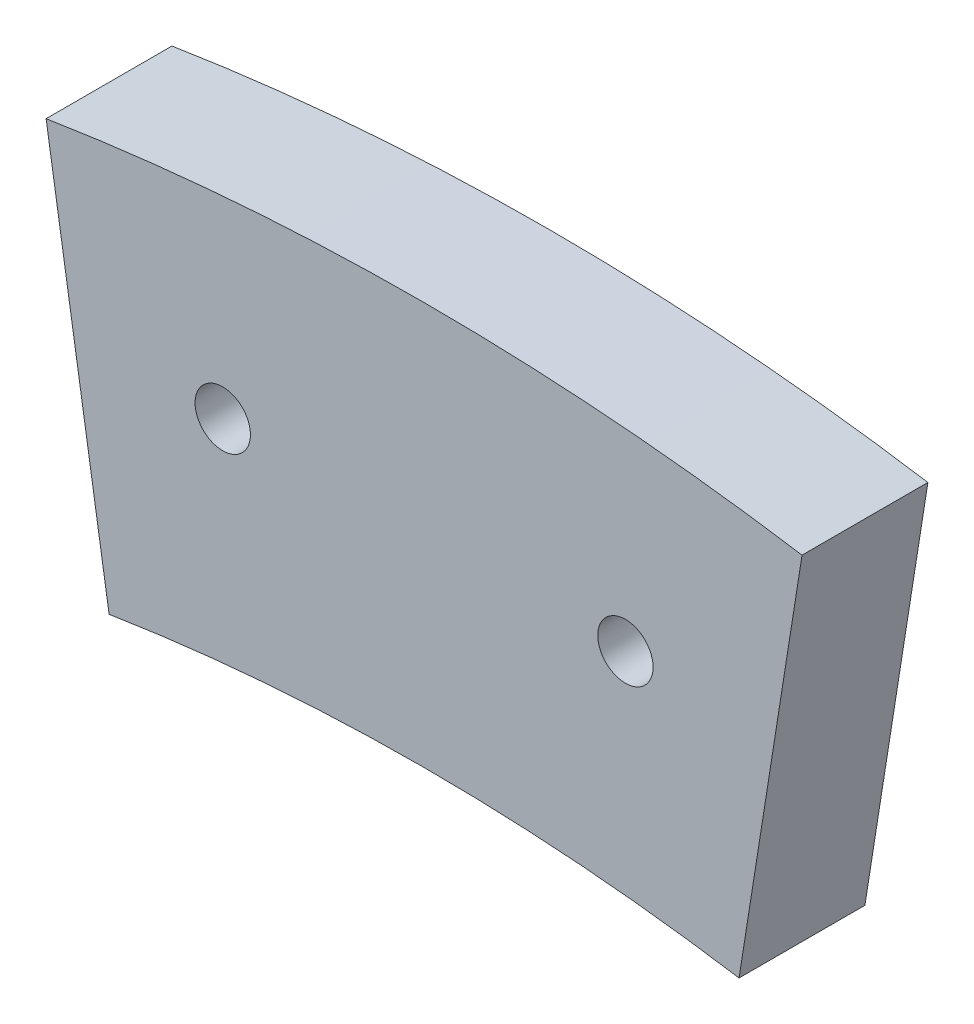
SolidWorks part; units mm, degrees
ref_plane "Front Plane" through (0, 0, 0) normal (0, 0, 1) x (1, 0, 0)
ref_plane "Top Plane" through (0, 0, 0) normal (0, 1, 0) x (1, 0, 0)
ref_plane "Right Plane" through (0, 0, 0) normal (1, 0, 0) x (0, 0, -1)
sketch "Sketch1" plane through (0, 0, 0) normal (0, 0, 1) x (1, 0, 0)
  line L0 (0, 0) -> (0, 96) construction
  line L1 (0, 0) -> (32.8339, 90.2105) construction
  line L2 (0, 0) -> (-6.116, 6.116) construction
  line L3 (0, 0) -> (-83.1384, 48) construction
  line L4 (-83.1384, 48) -> (-69.282, 40)
  line L5 (27.3616, 75.1754) -> (32.8339, 90.2105)
  line L6 (0, 0) -> (-15.0177, 94.8181) construction
  line L7 (0, 0) -> (15.0177, 94.8181) construction
  line L8 (0, 0) -> (-75.4804, 49.0175) construction
  line L9 (0, 0) -> (26.3135, 86.0674) construction
  line L10 (-15.0177, 94.8181) -> (-12.5148, 79.0151)
  line L11 (15.0177, 94.8181) -> (12.5148, 79.0151)
  line L12 (-27.3616, 75.1754) -> (0, 96) construction
  line L13 (-27.3616, 75.1754) -> (0, 96) construction
  line L14 (-21.1802, 88) -> (8, 88) construction
  line L15 (-75.4804, 49.0175) -> (-72.1257, 46.839)
  line L16 (-50.4006, 88.6785) -> (-43.5134, 76.5054)
  line L17 (0, 0) -> (-28.7074, 81.0672) construction
  line L18 (-30.0426, 84.8377) -> (-32.0455, 90.4936) construction
  line L19 (-34.2514, 96.1237) -> (-29.5682, 82.8988)
  line L20 (-34.2514, 96.1237) -> (-33.8743, 96.2573)
  line L22 (-33.8743, 96.2573) -> (-29.1911, 83.0323)
  line L23 (-34.2514, 96.1237) -> (-29.8395, 84.8634) construction
  line L24 (-30.2166, 84.7299) -> (-33.8743, 96.2573) construction
  line L25 (-25.3461, 98.8012) -> (-21.8442, 85.2603)
  line L26 (-25.7334, 98.7011) -> (-22.2314, 85.1601)
  line L27 (-22.7288, 87.0833) -> (-22.3416, 87.1834)
  line L28 (-16.6396, 100.6344) -> (-14.3311, 86.8395)
  line L29 (-17.0663, 100.563) -> (-14.7579, 86.768)
  line L30 (-14.6614, 88.7978) -> (-14.659, 88.799)
  line L31 (-25.7334, 98.7011) -> (-25.3461, 98.8012)
  line L32 (-17.0663, 100.563) -> (-16.6396, 100.6344)
  line L33 (-37.1397, 81.9801) -> (-37.5037, 81.8143)
  line L38 (-42.48, 92.7338) -> (-36.6799, 80.0067)
  line L39 (-42.116, 92.8997) -> (-36.3159, 80.1726)
  line L40 (-42.116, 92.8997) -> (-42.48, 92.7338)
  line L41 (42.116, 92.8997) -> (36.3159, 80.1726)
  line L42 (42.48, 92.7338) -> (36.6799, 80.0067)
  line L44 (44.4908, 78.2349) -> (44.4904, 78.2343)
  line L45 (44.4882, 78.2355) -> (44.4908, 78.2349)
  line L46 (37.1397, 81.9801) -> (37.5037, 81.8143)
  line L47 (17.0663, 100.563) -> (16.6396, 100.6344)
  line L48 (17.0663, 100.563) -> (14.7579, 86.768)
  line L49 (16.6396, 100.6344) -> (14.3311, 86.8395)
  line L50 (30.2166, 84.7299) -> (33.8743, 96.2573) construction
  line L51 (34.2514, 96.1237) -> (29.8395, 84.8634) construction
  line L52 (30.0426, 84.8377) -> (32.0455, 90.4936) construction
  line L53 (42.116, 92.8997) -> (42.48, 92.7338)
  line L55 (25.7334, 98.7011) -> (25.3461, 98.8012)
  line L56 (14.6614, 88.7978) -> (14.659, 88.799)
  line L57 (22.7288, 87.0833) -> (22.3416, 87.1834)
  line L58 (25.7334, 98.7011) -> (22.2314, 85.1601)
  line L59 (25.3461, 98.8012) -> (21.8442, 85.2603)
  line L60 (33.8743, 96.2573) -> (29.1911, 83.0323)
  line L62 (34.2514, 96.1237) -> (33.8743, 96.2573)
  line L63 (34.2514, 96.1237) -> (29.5682, 82.8988)
  line L64 (-29.3797, 82.9658) -> (-30.0426, 84.8377) construction
  line L65 (-50.0525, 88.8755) -> (-43.1652, 76.7023)
  line L66 (-50.0525, 88.8755) -> (-50.4006, 88.6785)
  line L67 (-57.9377, 83.9484) -> (-50.0157, 72.4218)
  line L68 (-57.608, 84.1749) -> (-49.686, 72.6484)
  line L69 (-57.608, 84.1749) -> (-57.9377, 83.9484)
  line L70 (25.144, 82.2422) -> (26.3135, 86.0674)
  line L71 (-42.4988, 92.7728) -> (-36.6808, 80.0063)
  line L72 (-42.1348, 92.9386) -> (-36.3168, 80.1722)
  line L73 (-42.4988, 92.7728) -> (-42.1348, 92.9386)
  line L75 (-50.4227, 88.7157) -> (-43.5142, 76.5049)
  line L76 (-50.0746, 88.9127) -> (-43.166, 76.7019)
  line L77 (-50.4227, 88.7157) -> (-50.0746, 88.9127)
  line L79 (-57.9629, 83.9835) -> (-50.0164, 72.4213)
  line L80 (-57.6333, 84.2101) -> (-49.6868, 72.6478)
  line L81 (-57.9629, 83.9835) -> (-57.6333, 84.2101)
  line L83 (-65.062, 78.6121) -> (-56.138, 67.7865)
  line L84 (-64.7534, 78.8665) -> (-55.8294, 68.0409)
  line L85 (-65.062, 78.6121) -> (-64.7534, 78.8665)
  line L87 (-71.6659, 72.6424) -> (-61.8324, 62.6358)
  line L88 (-71.3806, 72.9228) -> (-61.5471, 62.9161)
  line L89 (-71.6659, 72.6424) -> (-71.3806, 72.9228)
  line L91 (-77.7244, 66.1199) -> (-67.0562, 57.0084)
  line L92 (-77.4647, 66.4241) -> (-66.7964, 57.3125)
  line L93 (-77.7244, 66.1199) -> (-77.4647, 66.4241)
  line L95 (-83.1914, 59.0942) -> (-71.7696, 50.9471)
  line L96 (-82.9591, 59.4198) -> (-71.5373, 51.2728)
  line L97 (-83.1914, 59.0942) -> (-82.9591, 59.4198)
  line L119 (0, 0) -> (-83.1384, -48) construction
  line L120 (0, 0) -> (-87.0055, -40.5714) construction
  line L121 (0, 0) -> (-90.2105, -32.8339) construction
  line L122 (0, 0) -> (-92.7289, -24.8466) construction
  line L123 (0, 0) -> (-94.5415, -16.6702) construction
  line L124 (0, 0) -> (-95.6347, -8.367) construction
  line L125 (0, 0) -> (-96, 0) construction
  line L126 (0, 0) -> (-95.6347, 8.367) construction
  line L127 (0, 0) -> (-94.5415, 16.6702) construction
  line L128 (0, 0) -> (-92.7289, 24.8466) construction
  line L129 (0, 0) -> (-90.2105, 32.8339) construction
  line L130 (-95.6514, 35.5491) -> (-82.5102, 30.6358) [skipped]
  line L131 (-95.5113, 35.9237) -> (-82.3701, 31.0105) [skipped]
  line L132 (0, 0) -> (-87.0055, 40.5714) construction
  line L133 (-98.2789, 27.4627) -> (-84.7594, 23.7134) [skipped]
  line L134 (-98.3857, 27.0772) -> (-84.8663, 23.328) [skipped]
  line L135 (-100.2984, 18.7926) -> (-86.5036, 16.2359) [skipped]
  line L136 (-100.3713, 18.3993) -> (-86.5765, 15.8426) [skipped]
  line L137 (-100.3713, 18.3993) -> (-100.2984, 18.7926) [skipped]
  line L138 (-98.3857, 27.0772) -> (-98.2789, 27.4627) [skipped]
  line L139 (-95.6514, 35.5491) -> (-95.5113, 35.9237) [skipped]
  line L140 (-92.1891, 43.7504) -> (-79.5261, 37.7104) [skipped]
  line L141 (-92.0169, 44.1114) -> (-79.3539, 38.0715) [skipped]
  line L142 (-92.1891, 43.7504) -> (-92.0169, 44.1114) [skipped]
  line L143 (-88.0252, 51.6187) -> (-87.8222, 51.9634) [skipped]
  line L144 (-77.4449, 45.8507) -> (-75.7338, 44.8428) [skipped]
  line L145 (-77.6479, 45.506) -> (-75.9368, 44.4981) [skipped]
  arc A2 (27.3616, 75.1754) -> (-69.282, 40) centre (0, 0) ccw
  arc A3 (29.4137, 80.8136) -> (13.4534, 84.9412) centre (0, 0) ccw
  arc A4 (30.7818, 84.5723) -> (14.0791, 88.892) centre (0, 0) ccw
  arc A5 (32.8339, 90.2105) -> (-83.1384, 48) centre (0, 0) ccw
  arc A7 (-14.0791, 88.892) -> (-77.9423, 45) centre (0, 0) ccw
  arc A8 (-13.4534, 84.9412) -> (-74.4782, 43) centre (0, 0) ccw
  circle A10 centre (8, 88) radius 1.1
  circle A11 centre (-8, 88) radius 1.1
  arc A13 (-73.8149, 47.9359) -> (-76.2225, 44.0071) centre (0, 0) ccw
  arc A14 (-36.3159, 80.1726) -> (-36.6799, 80.0067) centre (0, 0) ccw
  arc A15 (-29.1911, 83.0323) -> (-29.5682, 82.8988) centre (0, 0) ccw
  arc A16 (-21.8442, 85.2603) -> (-22.2314, 85.1601) centre (0, 0) ccw
  arc A17 (-14.3311, 86.8395) -> (-14.7579, 86.768) centre (0, 0) ccw
  arc A18 (14.7579, 86.768) -> (14.3311, 86.8395) centre (0, 0) ccw
  arc A19 (22.2314, 85.1601) -> (21.8442, 85.2603) centre (0, 0) ccw
  arc A20 (29.5682, 82.8988) -> (29.1911, 83.0323) centre (0, 0) ccw
  arc A21 (36.6799, 80.0067) -> (36.3159, 80.1726) centre (0, 0) ccw
  arc A22 (-43.1652, 76.7023) -> (-43.5134, 76.5054) centre (0, 0) ccw
  arc A23 (-49.686, 72.6484) -> (-50.0157, 72.4218) centre (0, 0) ccw
  arc A24 (-36.3168, 80.1722) -> (-36.6808, 80.0063) centre (0, 0) ccw
  arc A25 (-43.166, 76.7019) -> (-43.5142, 76.5049) centre (0, 0) ccw
  arc A26 (-49.6868, 72.6478) -> (-50.0164, 72.4213) centre (0, 0) ccw
  arc A27 (-55.8294, 68.0409) -> (-56.138, 67.7865) centre (0, 0) ccw
  arc A28 (-61.5471, 62.9161) -> (-61.8324, 62.6358) centre (0, 0) ccw
  arc A29 (-66.7964, 57.3125) -> (-67.0562, 57.0084) centre (0, 0) ccw
  arc A30 (-71.5373, 51.2728) -> (-71.7696, 50.9471) centre (0, 0) ccw
  arc A31 (-75.7338, 44.8428) -> (-75.9368, 44.4981) centre (0, 0) ccw
  arc A36 (-86.5036, 16.2359) -> (-86.5765, 15.8426) centre (0, 0) ccw [skipped]
  arc A37 (-84.7594, 23.7134) -> (-84.8663, 23.328) centre (0, 0) ccw [skipped]
  arc A38 (-82.3701, 31.0105) -> (-82.5102, 30.6358) centre (0, 0) ccw [skipped]
  arc A39 (-79.3539, 38.0715) -> (-79.5261, 37.7104) centre (0, 0) ccw [skipped]
  point P28 (-30.0281, 84.7967)
  point P40 (-22.5352, 87.1334)
  point P45 (-14.8562, 88.766)
  point P55 (-44.3168, 78.3334)
  point P68 (44.3168, 78.3334)
  point P79 (14.8562, 88.766)
  point P80 (22.5352, 87.1334)
  point P81 (30.0281, 84.7967)
  point P106 (0, 0)
  point P169 (0, 0)
  dimension "D1" = 192
  dimension "D2" = 180
  dimension "D3" = 172
  dimension "D4" = 160
  dimension "D10" = 2.2
  dimension "D5" = 20
  dimension "D6" = 60
  dimension "D7" = 9
  dimension "D8" = 3
  dimension "D9" = 8
  dimension "D11" = 8
  dimension "D12" = 0.4
  dimension "D14" = 3
  dimension "D13" = 3
  dimension "D15" = 13
extrude "Boss-Extrude1" add sketch "Sketch1" along normal blind 5 contours L11 A5 L10 A2 A10 A11
